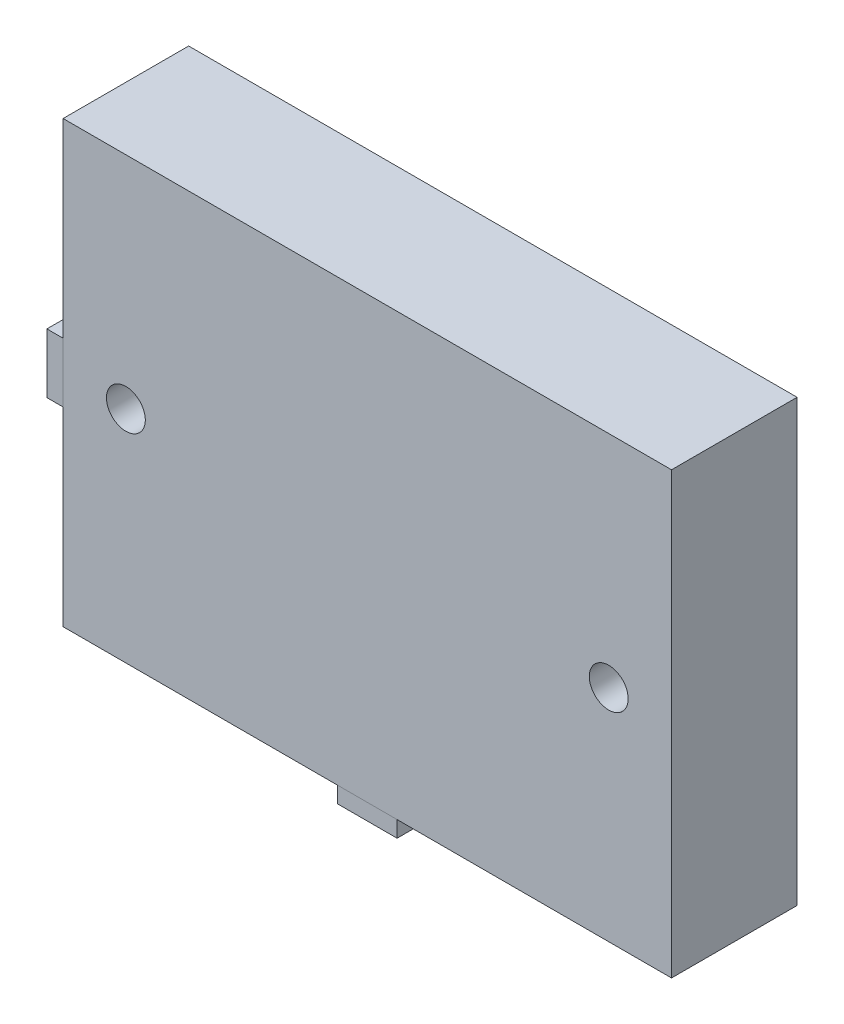
SolidWorks part; units mm, degrees
ref_plane "Plan de face" through (0, 0, 0) normal (0, 0, 1) x (1, 0, 0)
ref_plane "Plan de dessus" through (0, 0, 0) normal (0, 1, 0) x (1, 0, 0)
ref_plane "Plan de droite" through (0, 0, 0) normal (1, 0, 0) x (0, 0, -1)
sketch "Esquisse1" plane through (0, 0, 0) normal (0, 0, 1) x (1, 0, 0)
  line L1 (0, 0) -> (47, 0)
  line L2 (0, 0) -> (0, 34)
  line L3 (0, 34) -> (47, 34)
  line L4 (47, 0) -> (47, 34)
  dimension "D1" = 47
  dimension "D2" = 34
extrude "Boss.-Extru.1" add sketch "Esquisse1" along normal blind 9.7
sketch "Esquisse2" plane through (0, 0, 9.7) normal (0, 0, 1) x (1, 0, 0)
  line L0 (0, 17) -> (47, 17) construction
  line L1 (0, 34) -> (0, 0) construction
  line L2 (47, 0) -> (47, 34) construction
  line L3 (0, 17) -> (-6.378, 17) construction
  line L4 (-6.378, 17) -> (24.3807, 53.1665) construction
  line L5 (0, 14.7) -> (-1.25, 14.7)
  line L6 (-1.25, 14.7) -> (-1.25, 19.3)
  line L7 (0, 19.3) -> (-1.25, 19.3)
  line L8 (23.5, 0) -> (23.5, -4.6935) construction
  line L9 (0, 0) -> (47, 0) construction
  line L10 (21.2, -1.25) -> (25.8, -1.25)
  line L11 (25.8, -1.25) -> (25.8, 0)
  line L12 (0, 14.7) -> (0, 19.3)
  line L13 (25.8, 0) -> (21.2, 0)
  line L14 (21.2, -1.25) -> (21.2, 0)
  point P12 (-1.25, 17)
  point P21 (23.5, -1.25)
  dimension "D1" = 2.3
  dimension "D2" = 1.25
  dimension "D3" = 2.3
  dimension "D4" = 1.25
extrude "Boss.-Extru.2" add sketch "Esquisse2" against normal through all separate body
sketch "Esquisse3" plane through (0, 0, 9.7) normal (0, 0, 1) x (1, 0, 0)
  line L0 (0, 17) -> (47, 17) construction
  line L1 (0, 14.7) -> (0, 19.3) construction
  line L2 (47, 0) -> (47, 34) construction
  line L3 (23.5, 17) -> (23.5, 34) construction
  line L4 (47, 34) -> (0, 34) construction
  circle A0 centre (42.15, 17) radius 1.5
  circle A1 centre (4.85, 17) radius 1.5
  dimension "D1" = 18.65
extrude "Enlèv. mat.-Extru.1" cut sketch "Esquisse3" against normal through all
